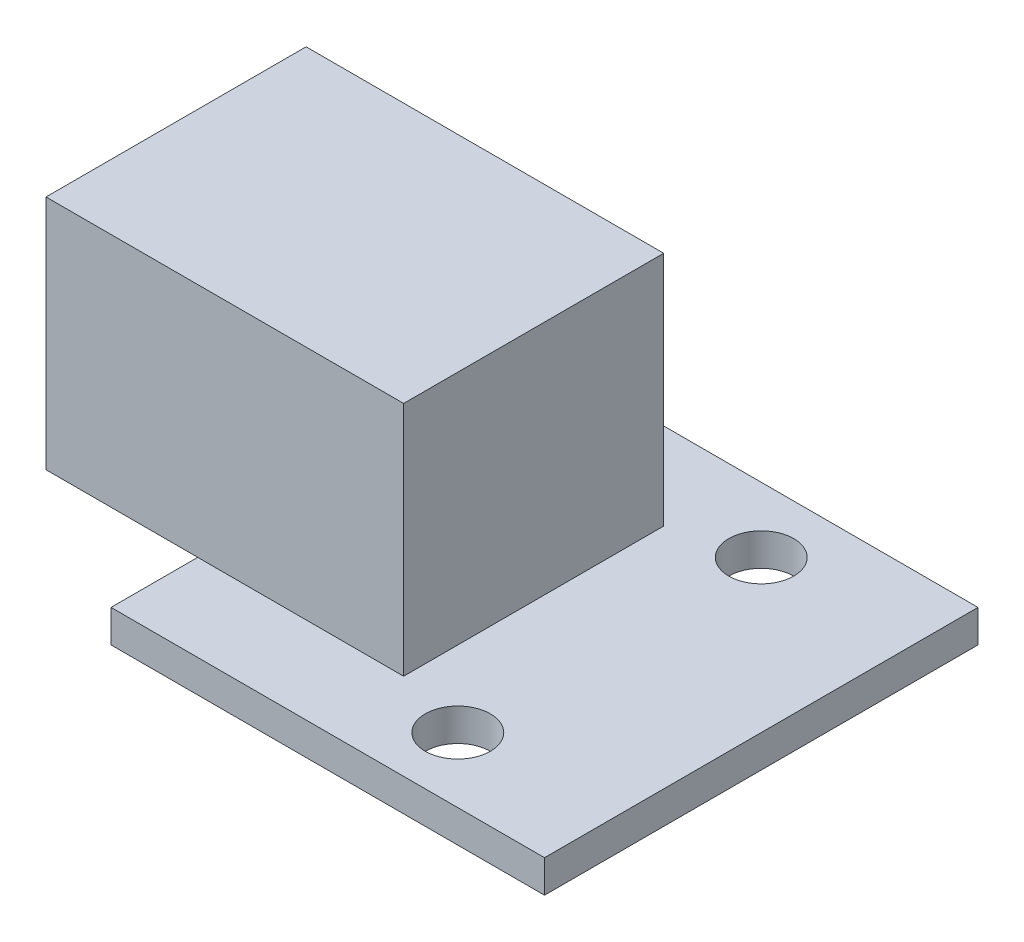
SolidWorks part; units mm, degrees
ref_plane "Front Plane" through (0, 0, 0) normal (0, 0, 1) x (1, 0, 0)
ref_plane "Top Plane" through (0, 0, 0) normal (0, 1, 0) x (1, 0, 0)
ref_plane "Right Plane" through (0, 0, 0) normal (1, 0, 0) x (0, 0, -1)
sketch "Sketch1" plane through (0, 0, 0) normal (0, 1, 0) x (1, 0, 0)
  line L0 (3, 7) -> (3, -7) construction
  line L1 (-10, -10) -> (10, -10)
  line L2 (-10, -10) -> (-10, 10)
  line L3 (-10, 10) -> (10, 10)
  line L4 (10, -10) -> (10, 10)
  line L5 (-10, -10) -> (10, 10) construction
  line L6 (-10, 10) -> (10, -10) construction
  circle A0 centre (3, 7) radius 1.5
  circle A1 centre (3, -7) radius 1.5
  point P0 (0, 0)
  point P10 (3, 0)
  dimension "D3" = 3
  dimension "D1" = 20
  dimension "D2" = 20
  dimension "D4" = 7
  dimension "D5" = 3
extrude "Boss-Extrude1" add sketch "Sketch1" along normal blind 1.5
sketch "Sketch2" plane through (0, 1.5, 0) normal (0, 1, 0) x (1, 0, 0)
  line L0 (-10, 10) -> (-10, -10) construction
  line L1 (-17, -6) -> (-0.5, -6)
  line L2 (-17, -6) -> (-17, 6)
  line L3 (-17, 6) -> (-0.5, 6)
  line L4 (-0.5, -6) -> (-0.5, 6)
  line L5 (-17, -6) -> (-0.5, 6) construction
  line L6 (-17, 6) -> (-0.5, -6) construction
  point P0 (-8.75, 0)
  dimension "D1" = 12
  dimension "D2" = 16.5
  dimension "D3" = 7
extrude "Boss-Extrude2" add sketch "Sketch2" along normal blind 10.9
